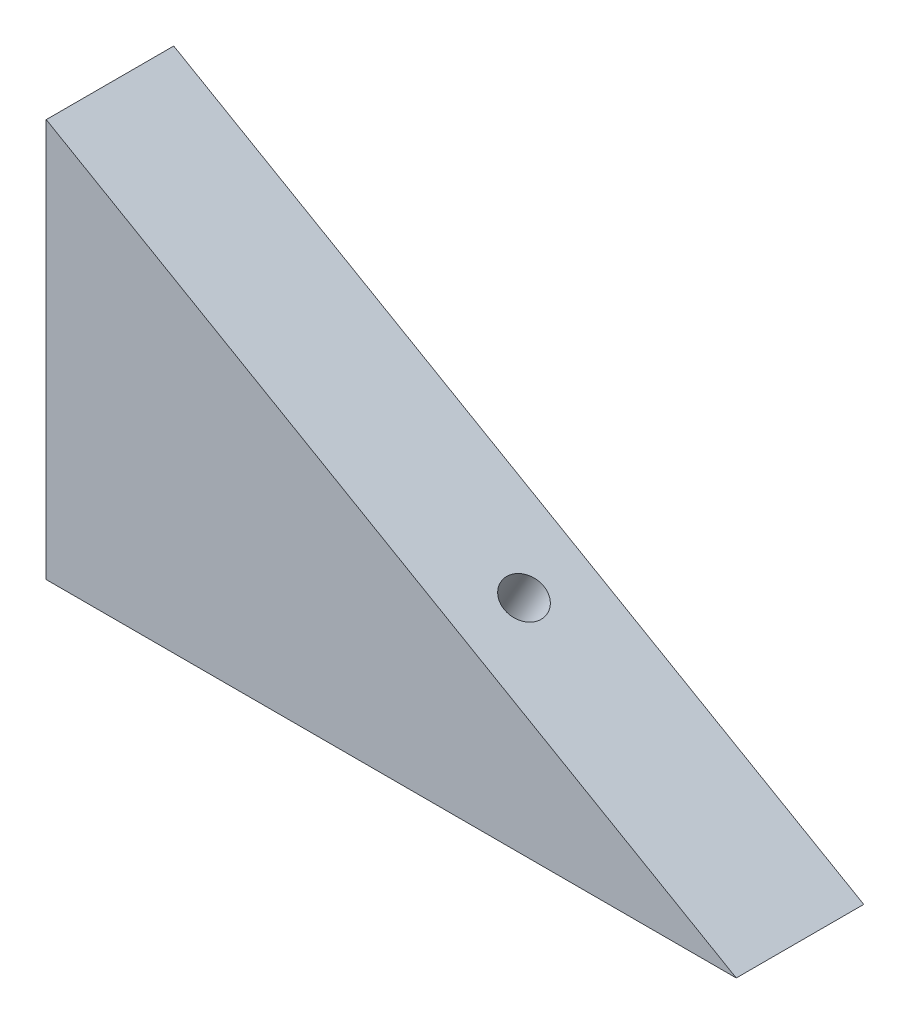
SolidWorks part; units mm, degrees
ref_plane "前视基准面" through (0, 0, 0) normal (0, 0, 1) x (1, 0, 0)
ref_plane "上视基准面" through (0, 0, 0) normal (0, 1, 0) x (1, 0, 0)
ref_plane "右视基准面" through (0, 0, 0) normal (1, 0, 0) x (0, 0, -1)
sketch "草图1" plane through (0, 0, 0) normal (0, 0, 1) x (1, 0, 0)
  line L0 (-42.303, -7.2358) -> (-42.303, -32.2358)
  line L1 (-42.303, -32.2358) -> (0.9983, -32.2358)
  line L2 (0.9983, -32.2358) -> (-42.303, -7.2358)
  dimension "D1" = 60
  dimension "D2" = 25
extrude "凸台-拉伸2" add sketch "草图1" along normal blind 8
hole_wizard "M3 螺纹孔1" positions "草图4" profile "草图5" tap size "M3" standard "GB"
sketch "草图4" plane through (-42.303, 0, 0) normal (-1, 0, 0) x (0, 0, 1)
  line L0 (8, -7.2358) -> (8, -32.2358) construction
  line L1 (8, -32.2358) -> (0, -32.2358) construction
  point P0 (4, -22.2358)
  dimension "D1" = 4
  dimension "D2" = 10
sketch "草图5" plane through (-42.303, -22.2358, 4) normal (0, 1, 0) x (0, 0, 1)
  line L0 (0, 0) -> (0, 5)
  line L1 (0, 5) -> (1.25, 5)
  line L2 (1.25, 5) -> (1.25, 0)
  line L5 (1.25, 0) -> (0, 0)
  line L10 (0, 5) -> (-1.25, 5) construction
  line L11 (0, -6.35) -> (0, 107.95) construction
  dimension "螺纹孔钻头直径" = 2.5
  dimension "螺纹孔钻头深度" = 5
  dimension "导头角度" = 180
cosmetic thread "孔螺蚊线1"
hole_wizard "M3 螺纹孔2" positions "草图6" profile "草图7" tap size "M3" standard "GB"
sketch "草图6" plane through (-13.709, -23.7446, 0) normal (0.5, 0.866, 0) x (0.866, -0.5, 0)
  line L0 (16.9825, 0) -> (-33.0175, 0) construction
  line L1 (16.9825, -8) -> (16.9825, 0) construction
  point P0 (-3.0175, -4)
  dimension "D1" = 4
  dimension "D2" = 20
sketch "草图7" plane through (-16.3222, -22.2358, 4) normal (0, 0, 1) x (-0.866, 0.5, 0)
  line L0 (0, 0) -> (0, 5)
  line L1 (0, 5) -> (1.25, 5)
  line L2 (1.25, 5) -> (1.25, 0)
  line L5 (1.25, 0) -> (0, 0)
  line L10 (0, 5) -> (-1.25, 5) construction
  line L11 (0, -6.35) -> (0, 107.95) construction
  dimension "螺纹孔钻头直径" = 2.5
  dimension "螺纹孔钻头深度" = 5
  dimension "导头角度" = 180
cosmetic thread "孔螺蚊线2"
